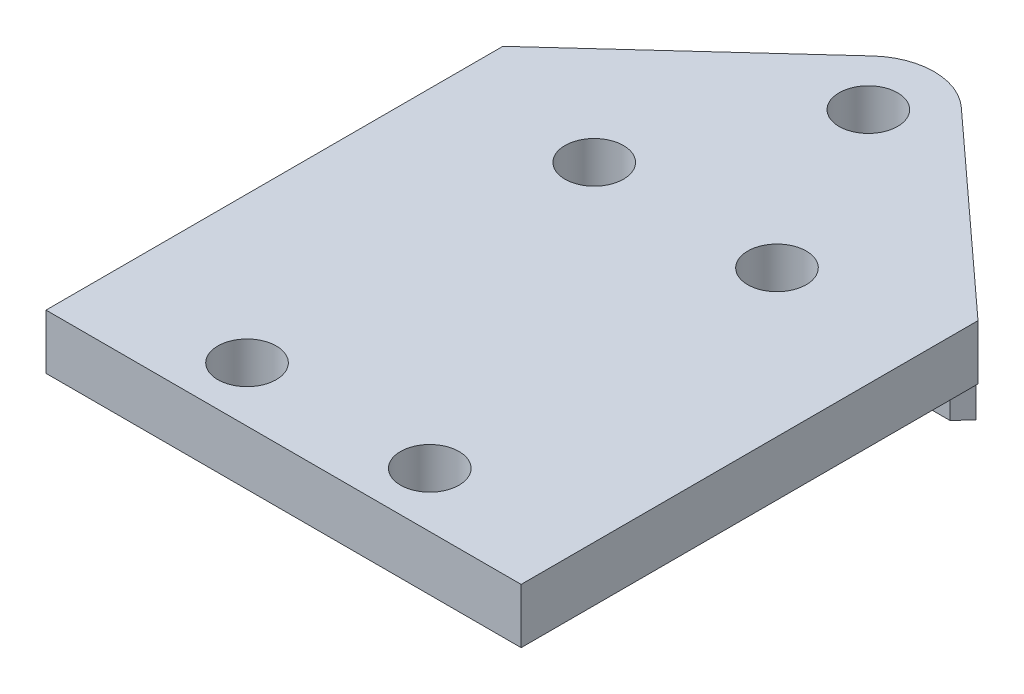
SolidWorks part; units mm, degrees
ref_plane "前视基准面" through (0, 0, 0) normal (0, 0, 1) x (1, 0, 0)
ref_plane "上视基准面" through (0, 0, 0) normal (0, 1, 0) x (1, 0, 0)
ref_plane "右视基准面" through (0, 0, 0) normal (1, 0, 0) x (0, 0, -1)
sketch "草图2" plane through (0, 0, 0) normal (0, 1, 0) x (1, 0, 0)
  line L0 (13, 31.2) -> (13, -7.8287) construction
  line L1 (0, 0) -> (26, 0)
  line L2 (0, 0) -> (0, 25)
  line L4 (26, 0) -> (26, 25)
  line L5 (4.5, 12.5) -> (26, 12.5) construction
  line L6 (0, 25) -> (10.5719, 34.6579)
  line L7 (26, 25) -> (15.4281, 34.6579)
  circle A0 centre (8, 22) radius 1.6
  circle A1 centre (18, 22) radius 1.6
  circle A2 centre (18, 3) radius 1.6
  circle A3 centre (8, 3) radius 1.6
  circle A4 centre (13, 32) radius 1.6
  arc A5 (15.4281, 34.6579) -> (10.5719, 34.6579) centre (13, 32) ccw
  dimension "D3" = 3.2
  dimension "D4" = 10
  dimension "D5" = 19
  dimension "D7" = 3.2
  dimension "D8" = 2
  dimension "D9" = 26
  dimension "D6" = 10
  dimension "D1" = 8
  dimension "D2" = 25
extrude "凸台-拉伸1" add sketch "草图2" along normal blind 3
sketch "草图3" plane through (0, 0, 0) normal (0, -1, 0) x (1, 0, 0)
  line L0 (2.03, -25.5) -> (23.97, -25.5)
  line L2 (26, -25) -> (15.4281, -34.6579) construction
  line L3 (24.6445, -26.2383) -> (15.4281, -34.6579)
  line L4 (10.5719, -34.6579) -> (0, -25) construction
  line L5 (10.5719, -34.6579) -> (1.3555, -26.2383)
  line L6 (1.3555, -26.2383) -> (2.03, -25.5)
  line L7 (24.6445, -26.2383) -> (23.97, -25.5)
  line L8 (13, -25.5) -> (13, -40.2215) construction
  circle A0 centre (13, -32) radius 1.6
  arc A2 (10.5719, -34.6579) -> (15.4281, -34.6579) centre (13, -32) ccw construction
  arc A3 (10.5719, -34.6579) -> (15.4281, -34.6579) centre (13, -32) ccw
  circle A4 centre (13, -32) radius 1.6 construction
  dimension "D1" = 0.5
  dimension "D2" = 1
extrude "凸台-拉伸2" add sketch "草图3" along normal blind 3
sketch "草图4" plane through (0, -3, 0) normal (0, -1, 0) x (1, 0, 0)
  line L2 (1.3555, -26.2383) -> (10.5719, -34.6579) construction
  line L3 (15.4281, -34.6579) -> (24.6445, -26.2383) construction
  line L4 (9.6737, -33.8374) -> (10.5719, -34.6579)
  line L5 (15.4281, -34.6579) -> (16.3263, -33.8374)
  arc A0 (16.3263, -33.8374) -> (9.5646, -30.3759) centre (13, -32) ccw
  circle A1 centre (13, -32) radius 1.6
  arc A2 (10.5719, -34.6579) -> (15.4281, -34.6579) centre (13, -32) ccw construction
  arc A3 (10.5719, -34.6579) -> (15.4281, -34.6579) centre (13, -32) ccw
  arc A4 (9.5646, -30.3759) -> (9.6737, -33.8374) centre (13, -32) ccw
  circle A5 centre (13, -32) radius 1.6 construction
  point P1 (0, 0)
  point P6 (11.9109, -28.393)
  point P15 (0, 0)
  dimension "D1" = 2.2
extrude "凸台-拉伸3" add sketch "草图4" along normal blind 5
